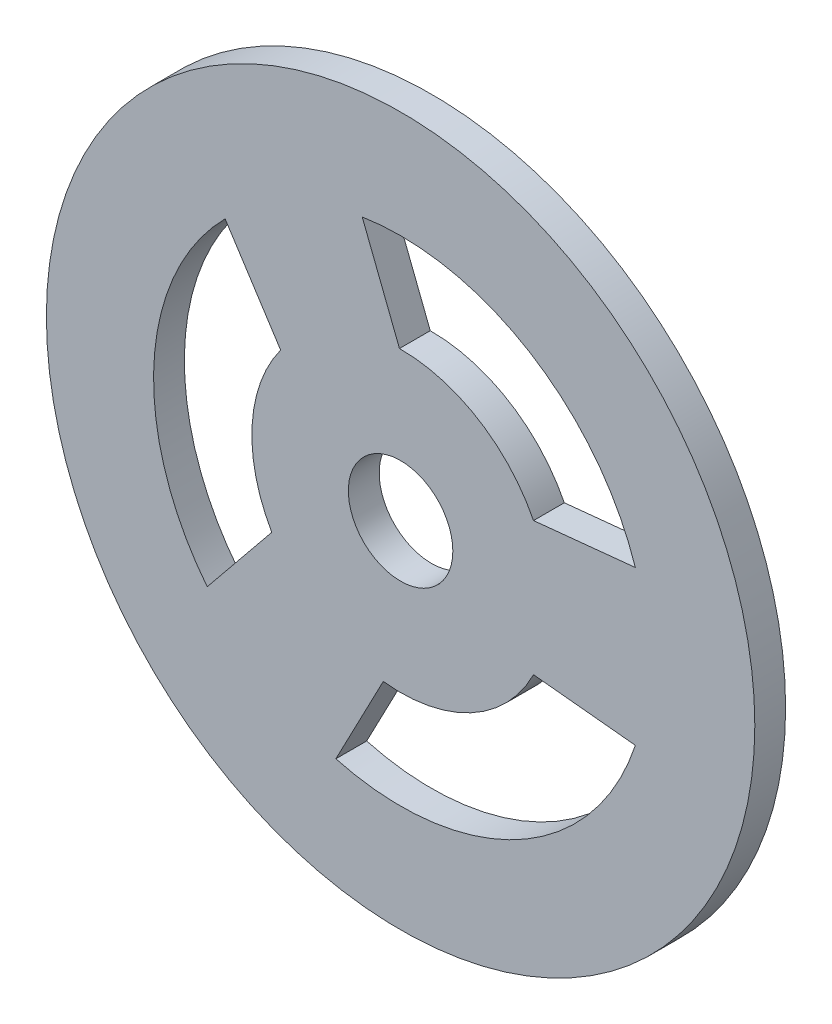
SolidWorks part; units mm, degrees
ref_plane "Front" through (0, 0, 0) normal (0, 0, 1) x (1, 0, 0)
ref_plane "Top" through (0, 0, 0) normal (0, 1, 0) x (1, 0, 0)
ref_plane "Right" through (0, 0, 0) normal (1, 0, 0) x (0, 0, -1)
sketch "Sketch1" plane through (0, 0, 0) normal (0, 0, 1) x (1, 0, 0)
  line L0 (268.439, -83.0806) -> (278.3553, -84.0806)
  line L1 (242.9468, -83.8194) -> (236.6592, -91.5524)
  line L2 (253.8054, -90.9673) -> (249.1883, -99.7999)
  line L5 (251.7556, -52.8125) -> (255.3829, -62.0956)
  line L6 (238.4025, -59.6459) -> (243.8102, -68.0179)
  line L7 (278.3553, -69.0806) -> (268.439, -70.0806)
  circle A0 centre (255.4938, -76.5806) radius 34.5
  arc A1 (238.4025, -59.6459) -> (236.6592, -91.5524) centre (255.4938, -76.5806) ccw
  arc A2 (243.8102, -68.0179) -> (242.9468, -83.8194) centre (255.4938, -76.5806) ccw
  arc A3 (253.8054, -90.9673) -> (268.439, -83.0806) centre (255.4938, -76.5806) ccw
  arc A4 (249.1883, -99.7999) -> (278.3553, -84.0806) centre (255.4938, -76.5806) ccw
  arc A5 (268.439, -70.0806) -> (255.3829, -62.0956) centre (255.4938, -76.5806) ccw
  arc A6 (278.3553, -69.0806) -> (251.7556, -52.8125) centre (255.4938, -76.5806) ccw
  circle A7 centre (255.4938, -76.5806) radius 5.0871
  dimension "D7" = 69
  dimension "D1" = 13
  dimension "D2" = 13
  dimension "D3" = 13
  dimension "D4" = 15
  dimension "D5" = 15
  dimension "D6" = 15
extrude "Base-Extrude" add sketch "Sketch1" along normal blind 3
